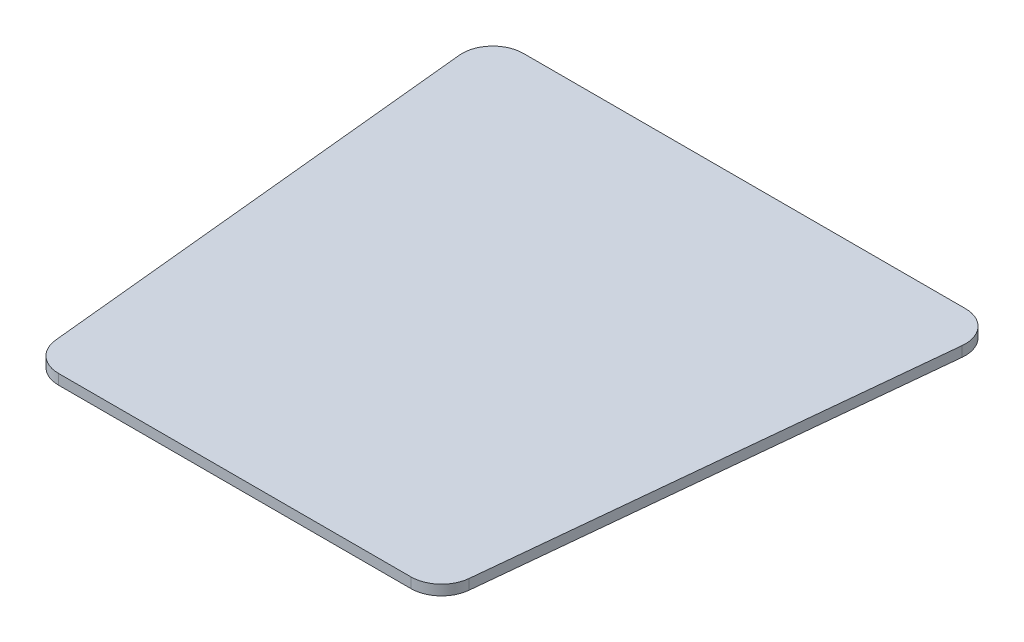
SolidWorks part; units mm, degrees
ref_plane "Front Plane" through (0, 0, 0) normal (0, 0, 1) x (1, 0, 0)
ref_plane "Top Plane" through (0, 0, 0) normal (0, 1, 0) x (1, 0, 0)
ref_plane "Right Plane" through (0, 0, 0) normal (1, 0, 0) x (0, 0, -1)
sketch "Sketch1" plane through (0, 0, 0) normal (0, 1, 0) x (1, 0, 0)
  line L0 (40, -50) -> (50, 50)
  line L1 (40, 50) -> (-40, 50)
  line L3 (40, -50) -> (-40, -50)
  line L5 (40, 50) -> (-40, -50) construction
  line L6 (40, -50) -> (-40, 50) construction
  line L7 (50, 50) -> (40, 50)
  line L8 (-40, 50) -> (-50, 50)
  line L9 (-50, 50) -> (-40, -50)
  line L10 (-40, 50) -> (-40, -50) construction
  line L11 (40, 50) -> (40, -50) construction
  point P0 (0, 0)
  dimension "D1" = 100
  dimension "D2" = 80
  dimension "D3" = 10
  dimension "D4" = 10
extrude "Boss-Extrude1" add sketch "Sketch1" along normal blind 2
fillet "Fillet1" radius 6 4 edges at (50, 1, -50) (40, 1, 50) (-40, 1, 50) (-50, 1, -50)
